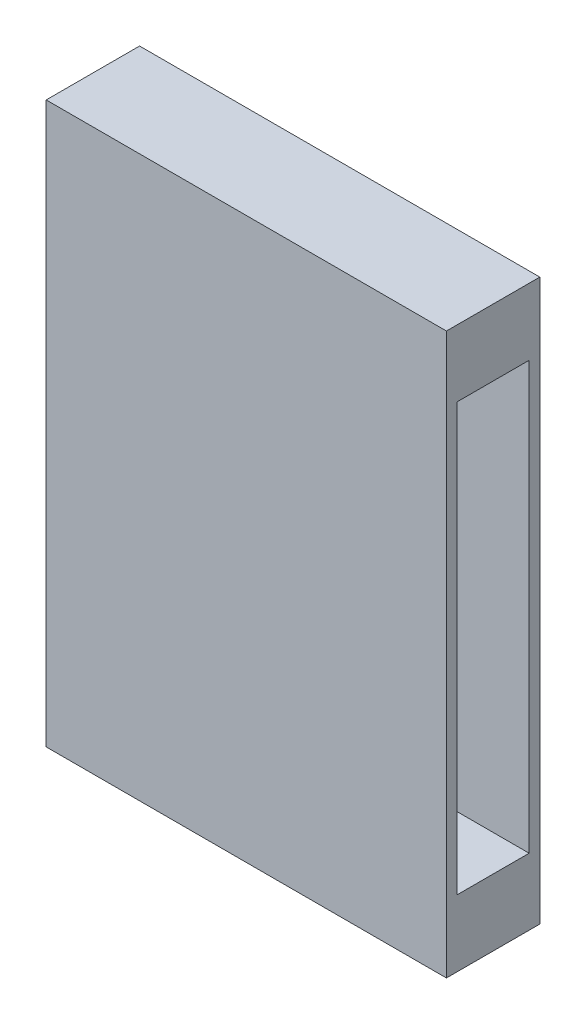
SolidWorks part; units mm, degrees
ref_plane "Top Plane" through (0, 0, 0) normal (0, 0, 1) x (1, 0, 0)
ref_plane "Front Plane" through (0, 0, 0) normal (0, 1, 0) x (1, 0, 0)
ref_plane "Right Plane" through (0, 0, 0) normal (1, 0, 0) x (0, 0, -1)
sketch "Sketch1" plane through (0, 0, 0) normal (0, 0, 1) x (1, 0, 0)
  line L1 (0, 0) -> (30, 0)
  line L2 (0, 0) -> (0, 42)
  line L3 (0, 42) -> (30, 42)
  line L4 (30, 0) -> (30, 42)
  dimension "D1" = 42
  dimension "D2" = 30
extrude "Boss-Extrude1" add sketch "Sketch1" along normal blind 7
sketch "Sketch2" plane through (0, 0, 0) normal (-1, 0, 0) x (0, 0, 1)
  line L14 (0.8, 41.2) -> (0.8, 0.8)
  line L15 (0.8, 0.8) -> (6.2, 0.8)
  line L16 (6.2, 0.8) -> (6.2, 41.2)
  line L17 (6.2, 41.2) -> (0.8, 41.2)
  line L18 (0.8, 41.2) -> (0.8, 0.8)
  line L19 (0.8, 0.8) -> (6.2, 0.8)
  line L20 (6.2, 0.8) -> (6.2, 41.2)
  line L21 (6.2, 41.2) -> (0.8, 41.2)
  dimension "D1" = 0.8
extrude "Cut-Extrude1" cut sketch "Sketch2" against normal blind 21
sketch "Sketch3" plane through (30, 0, 0) normal (1, 0, 0) x (0, 0, -1)
  line L0 (-7, 0) -> (-7, 42) construction
  line L1 (-6.2, 37) -> (-0.8, 37)
  line L2 (-6.2, 37) -> (-6.2, 5)
  line L3 (-6.2, 5) -> (-0.8, 5)
  line L4 (-0.8, 37) -> (-0.8, 5)
  line L6 (0, 0) -> (0, 42) construction
  point P6 (-6.2, 21)
  point P7 (0, 21)
  dimension "D1" = 32
  dimension "D2" = 0.8
  dimension "D3" = 0.8
  dimension "D4" = 0
extrude "Cut-Extrude2" cut sketch "Sketch3" against normal blind 21
